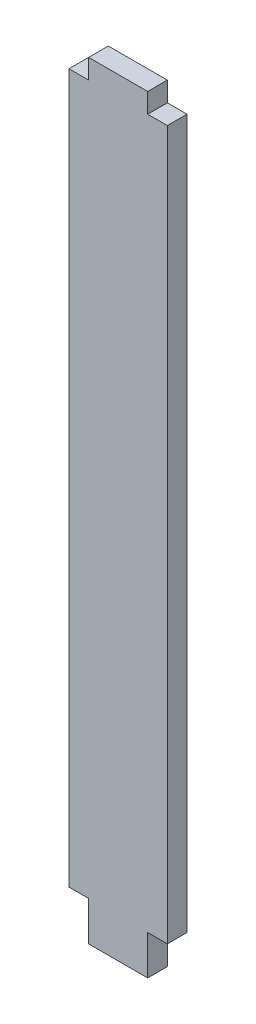
SolidWorks part; units mm, degrees
ref_plane "Front Plane" through (0, 0, 0) normal (0, 0, 1) x (1, 0, 0)
ref_plane "Top Plane" through (0, 0, 0) normal (0, 1, 0) x (1, 0, 0)
ref_plane "Right Plane" through (0, 0, 0) normal (1, 0, 0) x (0, 0, -1)
sketch "Sketch1" plane through (0, 0, 0) normal (0, 0, 1) x (1, 0, 0)
  line L3 (214.6309, 191.2074) -> (214.6309, 11.2074)
  line L5 (239.6309, 191.2074) -> (239.6309, 11.2074)
  line L6 (219.6309, 11.2074) -> (214.6309, 11.2074)
  line L7 (234.6309, 11.2074) -> (239.6309, 11.2074)
  line L9 (234.6309, 11.2074) -> (234.6309, 1.2074)
  line L13 (219.6309, 11.2074) -> (219.6309, 1.2074)
  line L17 (252.36, 102.5) -> (256.3433, 102.5) construction
  line L19 (219.6309, 191.2074) -> (219.6309, 196.2074)
  line L23 (234.6309, 191.2074) -> (234.6309, 196.2074)
  line L24 (157.1309, 196.2074) -> (277.1309, 196.2074) construction
  line L36 (219.6309, 196.2074) -> (234.6309, 196.2074)
  line L37 (234.6309, 191.2074) -> (239.6309, 191.2074)
  line L38 (214.6309, 191.2074) -> (219.6309, 191.2074)
  line L39 (234.6309, 1.2074) -> (219.6309, 1.2074)
  point P1 (227.36, 102.5)
  point P2 (0, 0)
  point P3 (0, 0)
  point P5 (0, 0)
  point P6 (234.9721, 8.7926)
  point P11 (0, 0)
  point P12 (234.6309, 1.2074)
  point P18 (0, 0)
  dimension "D1" = 5
  dimension "D2" = 25
  dimension "D3" = 15
  dimension "D4" = 5
  dimension "D5" = 10
  dimension "D6" = 10
  dimension "D7" = 5
extrude "Boss-Extrude1" add sketch "Sketch1" against normal blind 5
